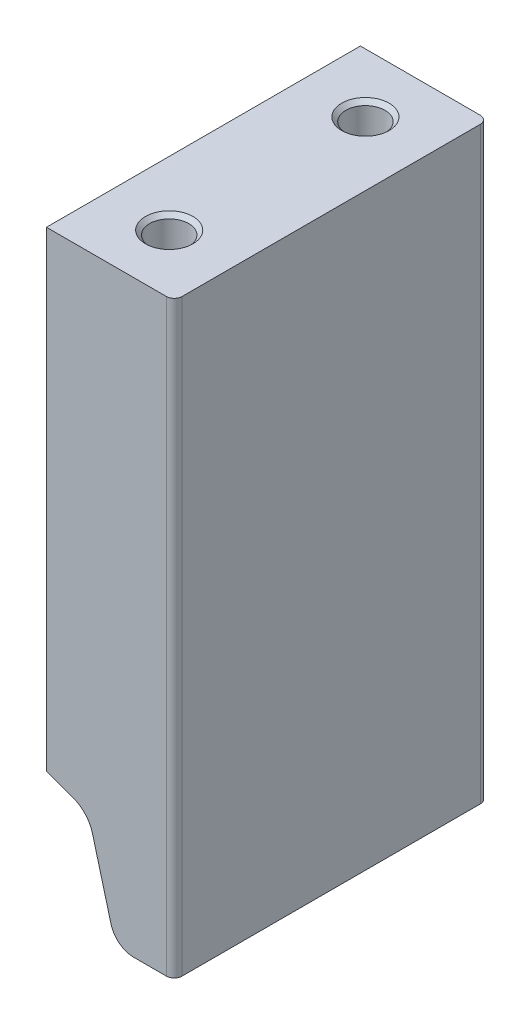
SolidWorks part; units mm, degrees
material "K110"
ref_plane "Front Plane" through (0, 0, 0) normal (0, 0, 1) x (1, 0, 0)
ref_plane "Top Plane" through (0, 0, 0) normal (0, 1, 0) x (1, 0, 0)
ref_plane "Right Plane" through (0, 0, 0) normal (1, 0, 0) x (0, 0, -1)
sketch "Sketch1" plane through (0, 0, 0) normal (0, 1, 0) x (1, 0, 0)
  line L1 (-8.14, -20) -> (8.14, -20)
  line L2 (-8.14, -20) -> (-8.14, 20)
  line L3 (-8.14, 20) -> (8.14, 20)
  line L4 (8.14, -20) -> (8.14, 20)
  line L5 (-8.14, -20) -> (8.14, 20) construction
  line L6 (-8.14, 20) -> (8.14, -20) construction
  point P0 (0, 0)
  dimension "D1" = 16.28
  dimension "D2" = 40
extrude "Boss-Extrude1" add sketch "Sketch1" against normal blind 75
sketch "Sketch2" plane through (0, 0, 20) normal (0, 0, 1) x (1, 0, 0)
  line L0 (-8.14, 0) -> (8.14, 0) construction
  line L1 (-8.14, -75) -> (-2.14, -75) construction
  line L2 (-8.14, -75) -> (-8.14, -61) construction
  line L3 (-8.14, -61) -> (-6.14, -61) construction
  line L4 (-2.14, -75) -> (-2.14, -65) construction
  line L5 (8.14, -75) -> (8.14, 0) construction
  line L6 (-4.7719, -61.2412) -> (-8.14, -60.0153)
  line L7 (-8.14, -75) -> (-8.14, 0) construction
  line L9 (0.6806, -75) -> (-8.14, -75)
  line L10 (-8.14, -75) -> (-8.14, -60.0153)
  line L11 (-2.2763, -63.9647) -> (0.6806, -75)
  line L12 (-8.14, -75) -> (8.14, -75) construction
  arc A0 (-6.14, -61) -> (-2.14, -65) centre (-6.14, -65) cw construction
  arc A1 (-2.2763, -63.9647) -> (-4.7719, -61.2412) centre (-6.14, -65) ccw
  arc A2 (-2.14, -65) -> (-2.2763, -63.9647) centre (-6.14, -65) ccw construction
  dimension "D3" = 4
  dimension "D1" = 61
  dimension "D2" = 10.28
  dimension "D4" = 2
  dimension "D5" = 20
  dimension "D6" = 15
extrude "Cut-Extrude1" cut sketch "Sketch2" against normal up to next
fillet "Fillet1" radius 3 1 edges at (0.6806, -75, 0)
fillet "Fillet2" radius 1 2 edges at (8.14, -37.5, -20) (8.14, -37.5, 20)
hole_wizard "M6 Tapped Hole1" positions "Sketch5" profile "Sketch4" tap size "M6" standard "ISO"
sketch "Sketch5" plane through (0, 0, 0) normal (0, 1, 0) x (1, 0, 0)
  line L0 (7.14, 20) -> (-8.14, 20) construction
  line L1 (-8.14, -20) -> (7.14, -20) construction
  point P0 (0, 12.5)
  point P2 (0, -12.5)
  dimension "D1" = 7.5
  dimension "D2" = 7.5
sketch "Sketch4" plane through (0, 0, -12.5) normal (1, 0, 0) x (0, 0, 1)
  line L0 (0, 0) -> (0, 18.5022)
  line L1 (0, 18.5022) -> (2.5, 17)
  line L2 (2.5, 17) -> (2.5, 0.525)
  line L3 (2.5, 0.525) -> (3.025, 0)
  line L5 (3.025, 0) -> (0, 0)
  line L6 (-2.5, 0.525) -> (-3.025, 0) construction
  line L10 (0, 18.5022) -> (-2.5, 17) construction
  line L11 (0, -6.35) -> (0, 107.95) construction
  dimension "Tap Drill Dia." = 5
  dimension "Tap Drill Depth" = 17
  dimension "Near C'Sink Dia." = 6.05
  dimension "Near C'Sink Angle" = 90
  dimension "Drill Angle" = 118
cosmetic thread "Hole Thread1" parameters "D1"=12, "D2"=6
cosmetic thread "Hole Thread2" parameters "D1"=12, "D2"=6
ref_plane "Plane1" through (0, -50, 0) normal (0, 1, 0) x (1, 0, 0)
sketch "Sketch6" plane through (0, -50, 0) normal (0, 1, 0) x (1, 0, 0)
  line L0 (-8.14, 20) -> (-8.14, -20)
  line L1 (-8.14, 20) -> (-8.14, -20)
  line L2 (-8.14, -20) -> (7.14, -20)
  line L3 (-8.14, -20) -> (7.14, -20)
  line L4 (8.14, -19) -> (8.14, 19)
  line L5 (8.14, -19) -> (8.14, 19)
  line L6 (7.14, 20) -> (-8.14, 20)
  line L7 (7.14, 20) -> (-8.14, 20)
  arc A0 (7.14, -20) -> (8.14, -19) centre (7.14, -19) ccw
  arc A1 (7.14, -20) -> (8.14, -19) centre (7.14, -19) ccw
  arc A2 (8.14, 19) -> (7.14, 20) centre (7.14, 19) ccw
  arc A3 (8.14, 19) -> (7.14, 20) centre (7.14, 19) ccw
